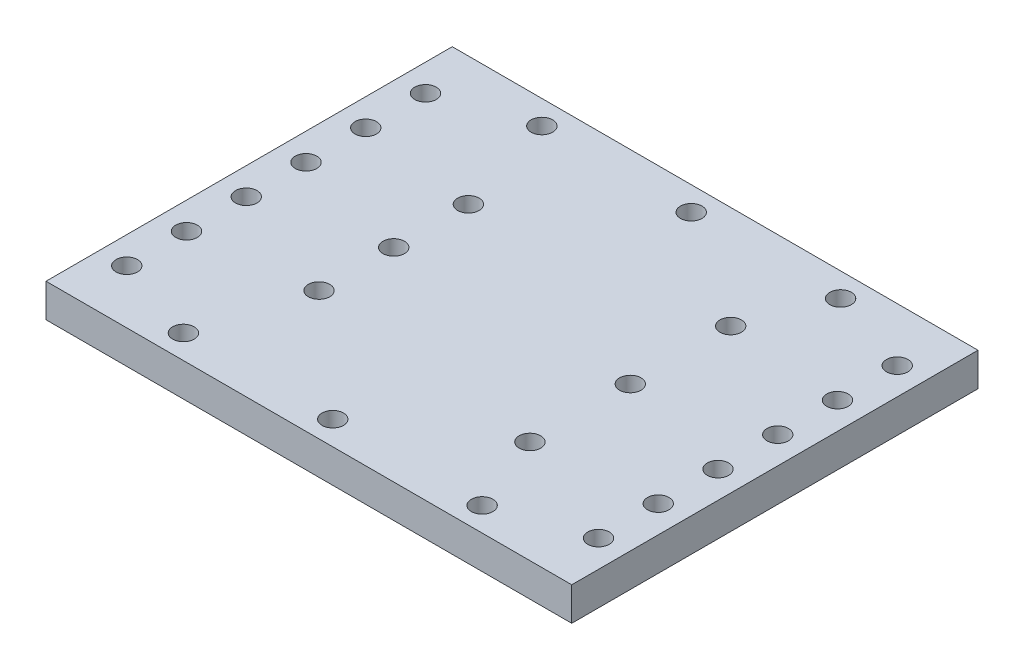
SolidWorks part; units mm, degrees
ref_plane "Front Plane" through (0, 0, 0) normal (0, 0, 1) x (1, 0, 0)
ref_plane "Top Plane" through (0, 0, 0) normal (0, 1, 0) x (1, 0, 0)
ref_plane "Right Plane" through (0, 0, 0) normal (1, 0, 0) x (0, 0, -1)
sketch "Sketch1" plane through (0, 0, 0) normal (0, 1, 0) x (1, 0, 0)
  line L1 (-87.1658, 33.45) -> (0.8342, 33.45)
  line L2 (-87.1658, 33.45) -> (-87.1658, -34.55)
  line L3 (-87.1658, -34.55) -> (0.8342, -34.55)
  line L4 (0.8342, 33.45) -> (0.8342, -34.55)
  dimension "D1" = 88
  dimension "D2" = 68
extrude "Boss-Extrude1" add sketch "Sketch1" along normal blind 5.588
sketch "Sketch2" plane through (0, 5.588, 0) normal (0, 1, 0) x (1, 0, 0)
  line L0 (-87.1658, -0.55) -> (0.8342, -0.55) construction
  line L1 (-87.1658, 33.45) -> (-87.1658, -34.55) construction
  line L2 (0.8342, -34.55) -> (0.8342, 33.45) construction
  line L3 (-43.1658, -34.55) -> (-43.1658, 33.45) construction
  line L4 (-87.1658, -34.55) -> (0.8342, -34.55) construction
  line L5 (0.8342, 33.45) -> (-87.1658, 33.45) construction
  circle A0 centre (-68.1658, 29.45) radius 1.8
  circle A1 centre (-43.1658, 29.45) radius 1.8
  circle A2 centre (-18.1658, 29.45) radius 1.8
  circle A3 centre (-43.1658, -30.55) radius 1.8
  circle A4 centre (-68.1658, -30.55) radius 1.8
  circle A5 centre (-18.1658, -30.55) radius 1.8
  circle A6 centre (-62.9658, -0.55) radius 1.8
  circle A7 centre (-23.3658, -0.55) radius 1.8
  circle A8 centre (-23.3658, -17.35) radius 1.8
  circle A9 centre (-23.3658, 16.25) radius 1.8
  circle A10 centre (-62.9658, -13.05) radius 1.8
  circle A11 centre (-62.9658, 11.95) radius 1.8
  circle A12 centre (-82.6458, 24.45) radius 1.8
  circle A13 centre (-3.6858, 24.45) radius 1.8
  circle A14 centre (-82.6458, 14.45) radius 1.8
  circle A15 centre (-3.6858, 14.45) radius 1.8
  circle A16 centre (-82.6458, 4.45) radius 1.8
  circle A17 centre (-3.6858, 4.45) radius 1.8
  circle A18 centre (-82.6458, -5.55) radius 1.8
  circle A19 centre (-3.6858, -5.55) radius 1.8
  circle A20 centre (-82.6458, -15.55) radius 1.8
  circle A21 centre (-3.6858, -15.55) radius 1.8
  circle A22 centre (-82.6458, -25.55) radius 1.8
  circle A23 centre (-3.6858, -25.55) radius 1.8
  dimension "D1" = 3.6
  dimension "D2" = 50
  dimension "D3" = 60
  dimension "D4" = 39.6
  dimension "D5" = 33.6
  dimension "D6" = 25
  dimension "D7" = 78.96
  dimension "D9" = 10
  dimension "D8" = 6
extrude "Cut-Extrude1" cut sketch "Sketch2" against normal through all
